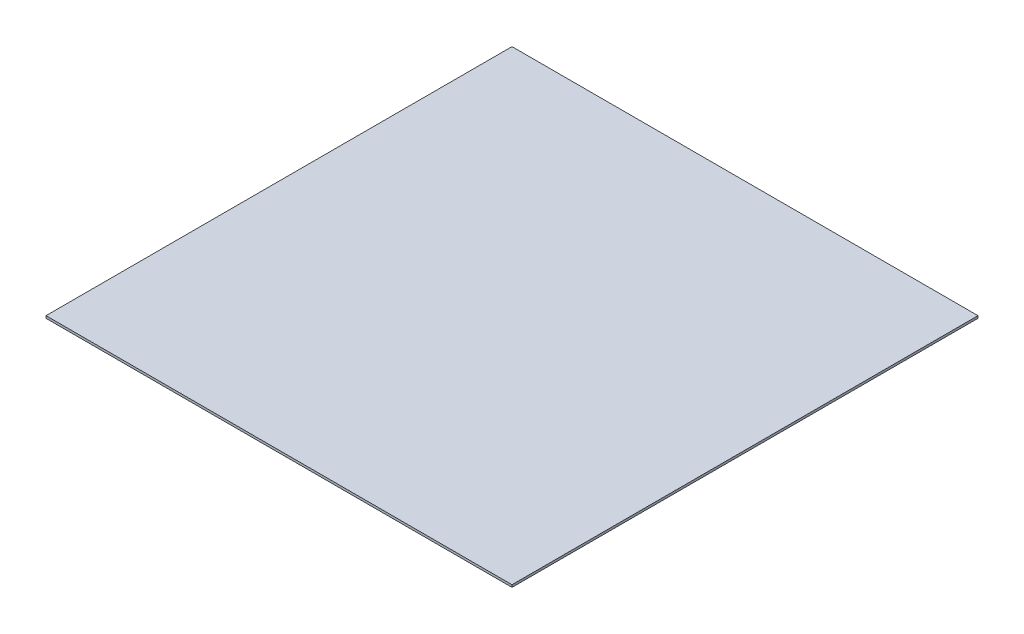
SolidWorks part; units mm, degrees
material "6061 Alloy"
ref_plane "Front Plane" through (0, 0, 0) normal (0, 0, 1) x (1, 0, 0)
ref_plane "Top Plane" through (0, 0, 0) normal (0, 1, 0) x (1, 0, 0)
ref_plane "Right Plane" through (0, 0, 0) normal (1, 0, 0) x (0, 0, -1)
sketch "Sketch1" plane through (0, 0, 0) normal (0, 1, 0) x (1, 0, 0)
  line L1 (-500, -500) -> (500, -500)
  line L2 (-500, -500) -> (-500, 500)
  line L3 (-500, 500) -> (500, 500)
  line L4 (500, -500) -> (500, 500)
  line L5 (-500, -500) -> (500, 500) construction
  line L6 (-500, 500) -> (500, -500) construction
  point P0 (0, 0)
  dimension "D1" = 1000
extrude "Boss-Extrude1" add sketch "Sketch1" along normal mid plane 5 contours L3 L4 L1 L2
